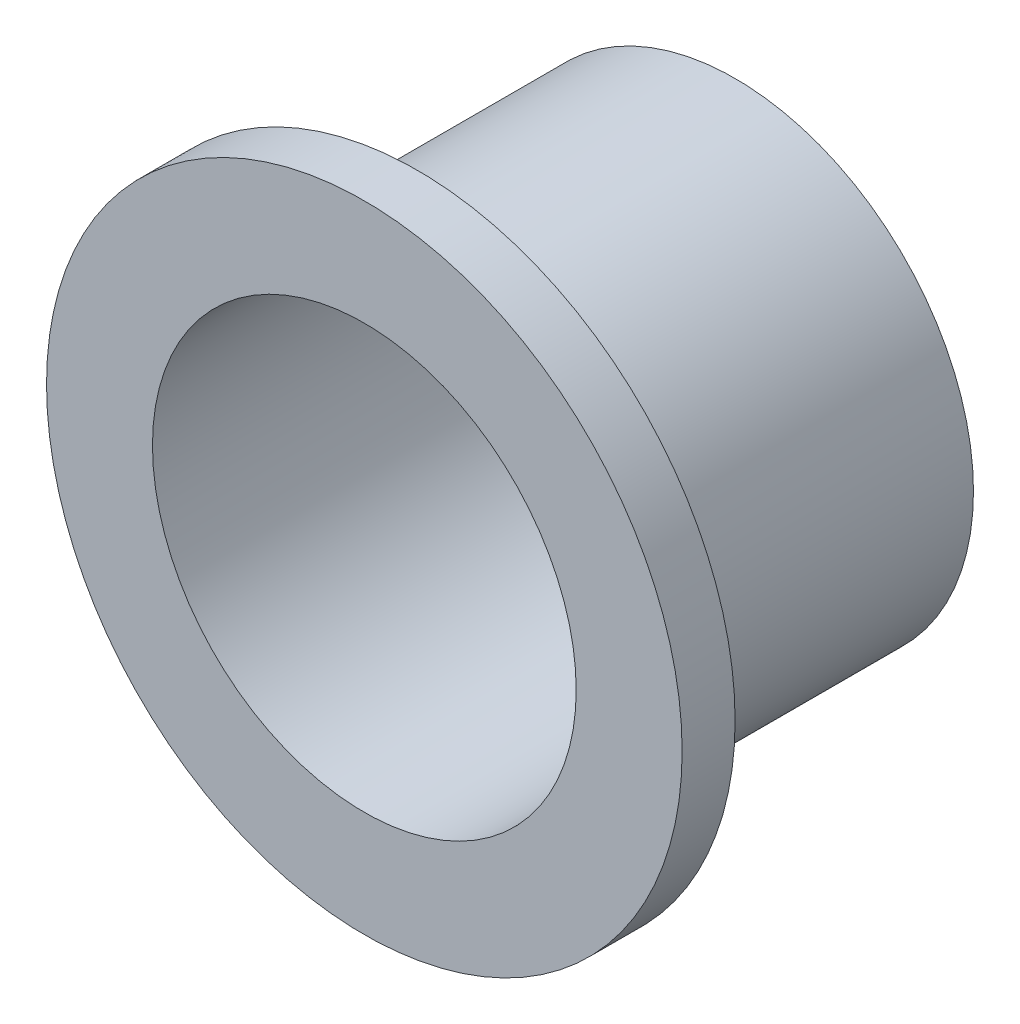
SolidWorks part; units mm, degrees
material "Copper"
ref_plane "Front Plane" through (0, 0, 0) normal (0, 0, 1) x (1, 0, 0)
ref_plane "Top Plane" through (0, 0, 0) normal (0, 1, 0) x (1, 0, 0)
ref_plane "Right Plane" through (0, 0, 0) normal (1, 0, 0) x (0, 0, -1)
sketch "Sketch1" plane through (0, 0, 0) normal (0, 0, 1) x (1, 0, 0)
  circle A0 centre (0, 0) radius 19.05
  dimension "D1" = 38.1
extrude "Boss-Extrude1" add sketch "Sketch1" along normal blind 22.225
sketch "Sketch2" plane through (0, 0, 0) normal (0, 0, -1) x (-1, 0, 0)
  circle A0 centre (0, 0) radius 14.2875
  circle A1 centre (0, 0) radius 19.05
  dimension "D1" = 28.575
extrude "Cut-Extrude1" cut sketch "Sketch2" against normal blind 19.05
sketch "Sketch3" plane through (0, 0, 22.225) normal (0, 0, 1) x (1, 0, 0)
  circle A0 centre (0, 0) radius 12.7
  dimension "D1" = 25.4
extrude "Cut-Extrude2" cut sketch "Sketch3" against normal through all
